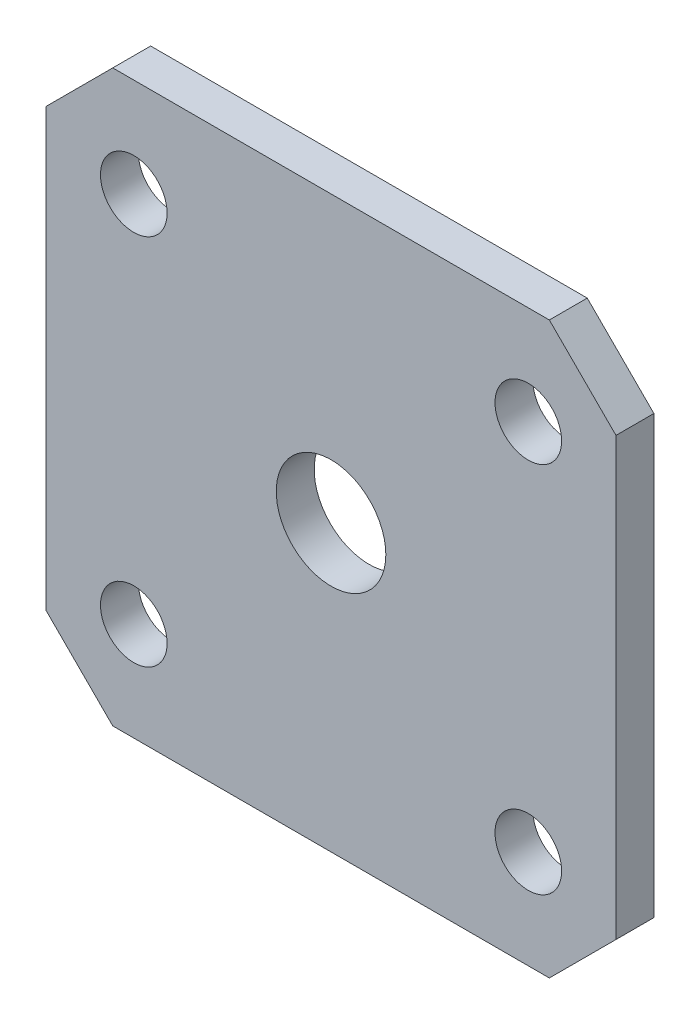
SolidWorks part; units mm, degrees
material "Plain Carbon Steel"
ref_plane "Front Plane" through (0, 0, 0) normal (0, 0, 1) x (1, 0, 0)
ref_plane "Top Plane" through (0, 0, 0) normal (0, 1, 0) x (1, 0, 0)
ref_plane "Right Plane" through (0, 0, 0) normal (1, 0, 0) x (0, 0, -1)
sketch "Sketch1" plane through (106.6392, 25.3769, 0) normal (0, 0, 1) x (1, 0, 0)
  line L1 (-41.275, 279.4) -> (41.275, 279.4)
  line L2 (-41.275, 279.4) -> (-41.275, 361.95)
  line L3 (-41.275, 361.95) -> (41.275, 361.95)
  line L4 (41.275, 279.4) -> (41.275, 361.95)
  line L5 (-41.275, 279.4) -> (41.275, 361.95) construction
  line L6 (-41.275, 361.95) -> (41.275, 279.4) construction
  circle A0 centre (-28.575, 347.6625) radius 4.826
  circle A1 centre (-28.575, 293.6875) radius 4.826
  circle A2 centre (28.575, 347.6625) radius 4.826
  circle A3 centre (28.575, 293.6875) radius 4.826
  circle A4 centre (0, 320.675) radius 7.9375
  point P0 (0, 320.675)
  dimension "D3" = 9.652
  dimension "D5" = 15.875
  dimension "D1" = 82.55
  dimension "D2" = 82.55
  dimension "D4" = 57.15
  dimension "D6" = 57.15
  dimension "D7" = 26.9875
  dimension "D8" = 53.975
  dimension "D9" = 28.575
extrude "Boss-Extrude1" add sketch "Sketch1" along normal blind 4.826 and the other way blind 0.6662
chamfer "Chamfer1" distance 9.652 angle 45 4 edges at (65.3642, 304.7769, 2.0799) (65.3642, 387.3269, 2.0799) (147.9142, 387.3269, 2.0799) (147.9142, 304.7769, 2.0799)
